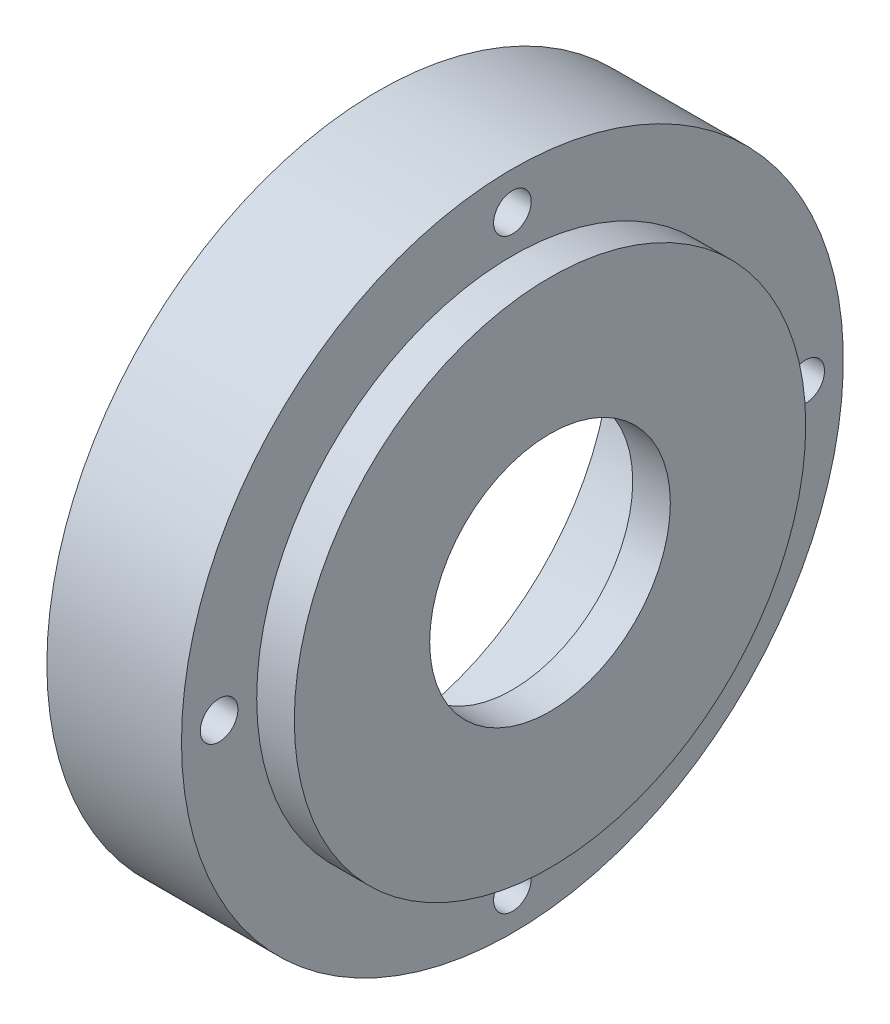
SolidWorks part; units mm, degrees
ref_plane "前视基准面" through (0, 0, 0) normal (0, 0, 1) x (1, 0, 0)
ref_plane "上视基准面" through (0, 0, 0) normal (0, 1, 0) x (1, 0, 0)
ref_plane "右视基准面" through (0, 0, 0) normal (1, 0, 0) x (0, 0, -1)
sketch "草图1" plane through (0, 0, 0) normal (1, 0, 0) x (0, 0, -1)
  circle A0 centre (0, 0) radius 31
  circle A1 centre (0, 0) radius 44
extrude "凸台-拉伸1" add sketch "草图1" along normal blind 17.9
sketch "草图2" plane through (17.9, 0, 0) normal (1, 0, 0) x (0, 0, -1)
  circle A0 centre (0, 39) radius 2.5
  circle A1 centre (39, 0) radius 2.5
  circle A2 centre (0, -39) radius 2.5
  circle A3 centre (-39, 0) radius 2.5
  point P11 (0, 0)
  dimension "D1" = 4
extrude "切除-拉伸1" cut sketch "草图2" against normal up to surface (17.9 mm away) up to face at (0, 0, -44)
sketch "草图3" plane through (17.9, 0, 0) normal (1, 0, 0) x (0, 0, -1)
  circle A0 centre (0, 0) radius 16
  circle A1 centre (0, 0) radius 34
extrude "凸台-拉伸2" add sketch "草图3" along normal blind 5
